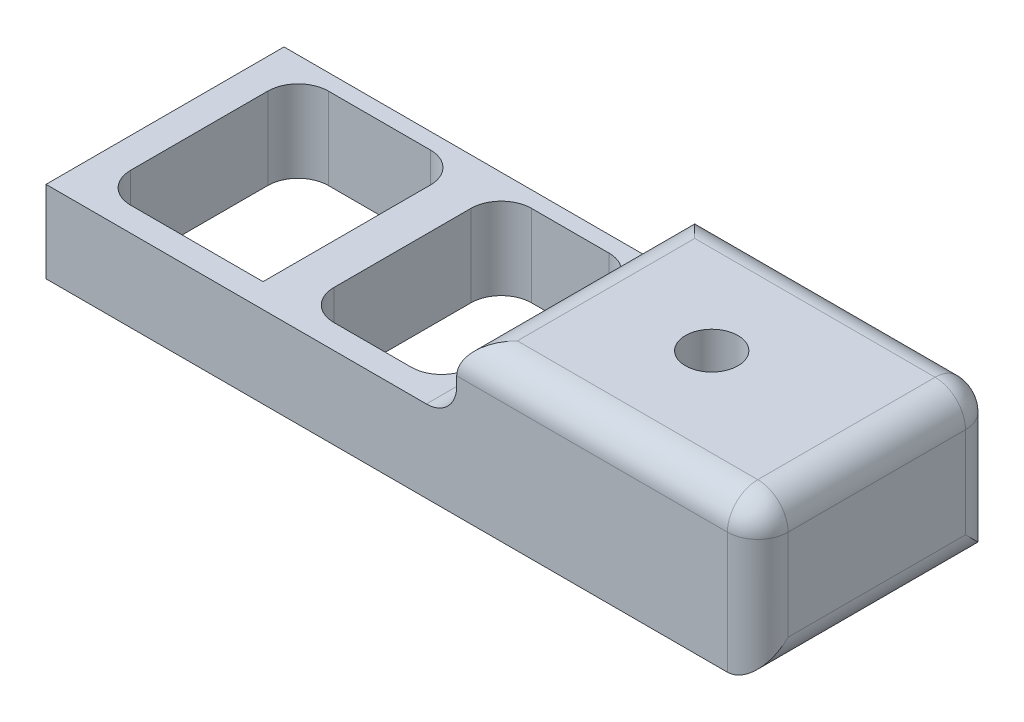
SolidWorks part; units mm, degrees
ref_plane "Front Plane" through (0, 0, 0) normal (0, 0, 1) x (1, 0, 0)
ref_plane "Top Plane" through (0, 0, 0) normal (0, 1, 0) x (1, 0, 0)
ref_plane "Right Plane" through (0, 0, 0) normal (1, 0, 0) x (0, 0, -1)
sketch "Sketch1" plane through (0, 0, 0) normal (0, 1, 0) x (1, 0, 0)
  line L0 (0, 0) -> (-36.0506, 0) construction
  line L1 (3.6201, -6.2433) -> (7.2169, 0.0134)
  line L2 (7.2169, 0.0134) -> (3.5968, 6.2567)
  line L3 (3.5968, 6.2567) -> (-3.6201, 6.2433)
  line L4 (-3.6201, 6.2433) -> (-7.2169, -0.0134)
  line L5 (-7.2169, -0.0134) -> (-3.5968, -6.2567)
  line L6 (-3.5968, -6.2567) -> (3.6201, -6.2433)
  line L7 (-36.0506, -7.8479) -> (-36.0506, 7.8479)
  line L8 (-36.0506, 7.8479) -> (10.8835, 7.8479)
  line L9 (10.8835, 7.8479) -> (10.8835, -7.8479)
  line L10 (10.8835, -7.8479) -> (-36.0506, -7.8479)
  circle A0 centre (0, 0) radius 6.25 construction
  point P1 (0.0116, -6.25)
  point P14 (-36.0506, 0)
  dimension "D1" = 12.5
extrude "Boss-Extrude1" add sketch "Sketch1" along normal blind 7 contours L5 L6 L1 L2 L3 L4 | L8 L9 L10 L7
sketch "Sketch2" plane through (0, 7, 0) normal (0, 1, 0) x (1, 0, 0)
  line L5 (-36.0506, 7.8479) -> (-36.0506, -7.8479)
  line L6 (-36.0506, -7.8479) -> (10.8835, -7.8479)
  line L7 (10.8835, -7.8479) -> (10.8835, 7.8479)
  line L8 (10.8835, 7.8479) -> (-36.0506, 7.8479)
  line L9 (-36.0506, 7.8479) -> (-36.0506, -7.8479)
  line L10 (-36.0506, -7.8479) -> (10.8835, -7.8479)
  line L11 (10.8835, -7.8479) -> (10.8835, 7.8479)
  line L12 (10.8835, 7.8479) -> (-36.0506, 7.8479)
  dimension "D1" = 0
extrude "Boss-Extrude2" add sketch "Sketch2" along normal blind 3
sketch "Sketch3" plane through (0, 0, 7.8479) normal (0, 0, 1) x (1, 0, 0)
  line L1 (-41.7058, 5.3962) -> (-8.9677, 5.3962)
  line L2 (-41.7058, 5.3962) -> (-41.7058, 12.0017)
  line L3 (-41.7058, 12.0017) -> (-8.9677, 12.0017)
  line L4 (-8.9677, 5.3962) -> (-8.9677, 12.0017)
extrude "Cut-Extrude1" cut sketch "Sketch3" against normal through all
sketch "Sketch4" plane through (0, 5.3962, 0) normal (0, 1, 0) x (1, 0, 0)
  line L1 (-20.6687, -6.2485) -> (-11.565, -6.2485)
  line L2 (-20.6687, -6.2485) -> (-20.6687, 6.7889)
  line L3 (-20.6687, 6.7889) -> (-11.565, 6.7889)
  line L4 (-11.565, -6.2485) -> (-11.565, 6.7889)
  line L5 (-23.3383, -6.2485) -> (-34.0647, -6.2485)
  line L6 (-23.3383, -6.2485) -> (-23.3383, 6.7889)
  line L7 (-23.3383, 6.7889) -> (-34.0647, 6.7889)
  line L8 (-34.0647, -6.2485) -> (-34.0647, 6.7889)
extrude "Cut-Extrude2" cut sketch "Sketch4" against normal blind 10
fillet "Fillet1" radius 2 15 edges at (10.8835, 5, 7.8479) (10.8835, 5, -7.8479) (10.8835, 0, 0) (0.9579, 10, -7.8479) (10.8835, 10, 0) (0.9579, 10, 7.8479) (-8.9677, 10, 0) (-8.9677, 5.3962, 0) (-34.0647, 2.6981, 6.2485) (-34.0647, 2.6981, -6.7889) (-23.3383, 2.6981, -6.7889) (-20.6687, 2.6981, 6.2485) (-20.6687, 2.6981, -6.7889) (-11.565, 2.6981, 6.2485) (-11.565, 2.6981, -6.7889)
sketch "Sketch5" plane through (0, 10, 0) normal (0, 1, 0) x (1, 0, 0)
  circle A0 centre (0, 0) radius 1.7326
extrude "Cut-Extrude3" cut sketch "Sketch5" against normal blind 10
